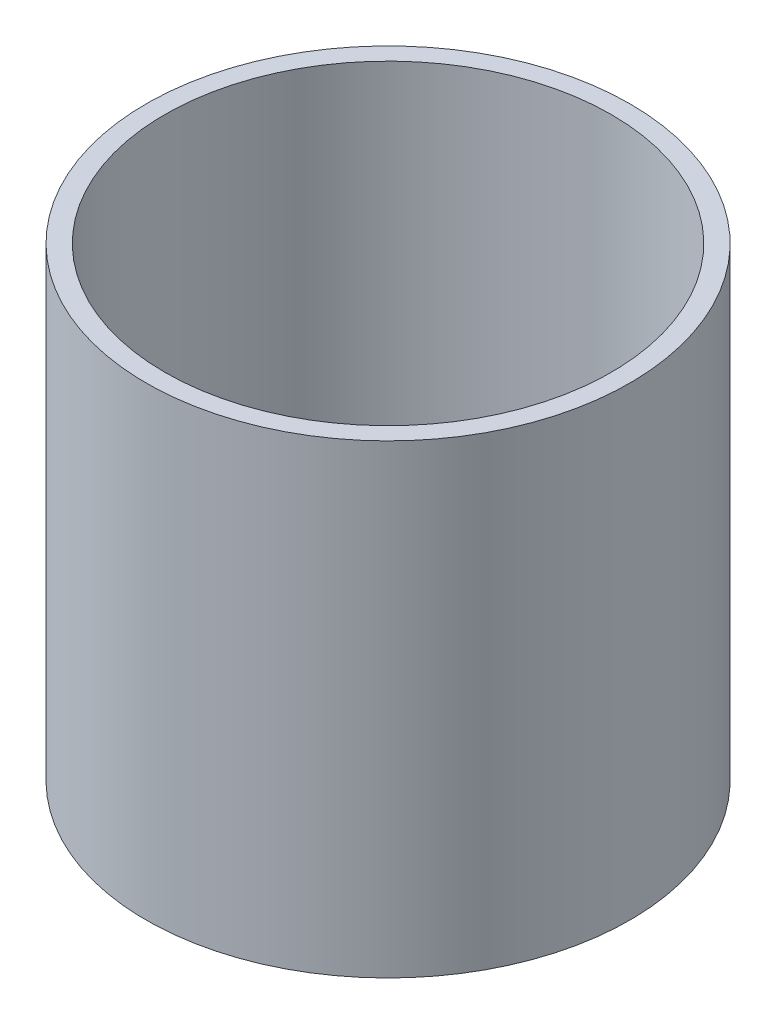
SolidWorks part; units mm, degrees
ref_plane "Front Plane" through (0, 0, 0) normal (0, 0, 1) x (1, 0, 0)
ref_plane "Top Plane" through (0, 0, 0) normal (0, 1, 0) x (1, 0, 0)
ref_plane "Right Plane" through (0, 0, 0) normal (1, 0, 0) x (0, 0, -1)
sketch "Sketch1" plane through (0, 0, 0) normal (0, 1, 0) x (1, 0, 0)
  circle A0 centre (0, 0) radius 38.1
  dimension "D1" = 76.2
extrude "Boss-Extrude1" add sketch "Sketch1" along normal blind 76.2
shell "Shell2" thickness 3.175
scale "Scale1" bodies to scale 101 scale about centroid uniform scaling yes scale factor 0.615385
ref_plane "Plane2" through (0, -5.334, 0) normal (0, 1, 0) x (1, 0, 0)
sketch "Sketch4" plane through (0, -5.334, 0) normal (0, 1, 0) x (1, 0, 0)
  line L1 (50.8, 50.8) -> (-50.8, 50.8)
  line L2 (50.8, 50.8) -> (50.8, -50.8)
  line L3 (50.8, -50.8) -> (-50.8, -50.8)
  line L4 (-50.8, 50.8) -> (-50.8, -50.8)
  line L5 (50.8, 50.8) -> (-50.8, -50.8) construction
  line L6 (50.8, -50.8) -> (-50.8, 50.8) construction
  point P0 (0, 0)
  dimension "D1" = 101.6
  dimension "D2" = 101.6
